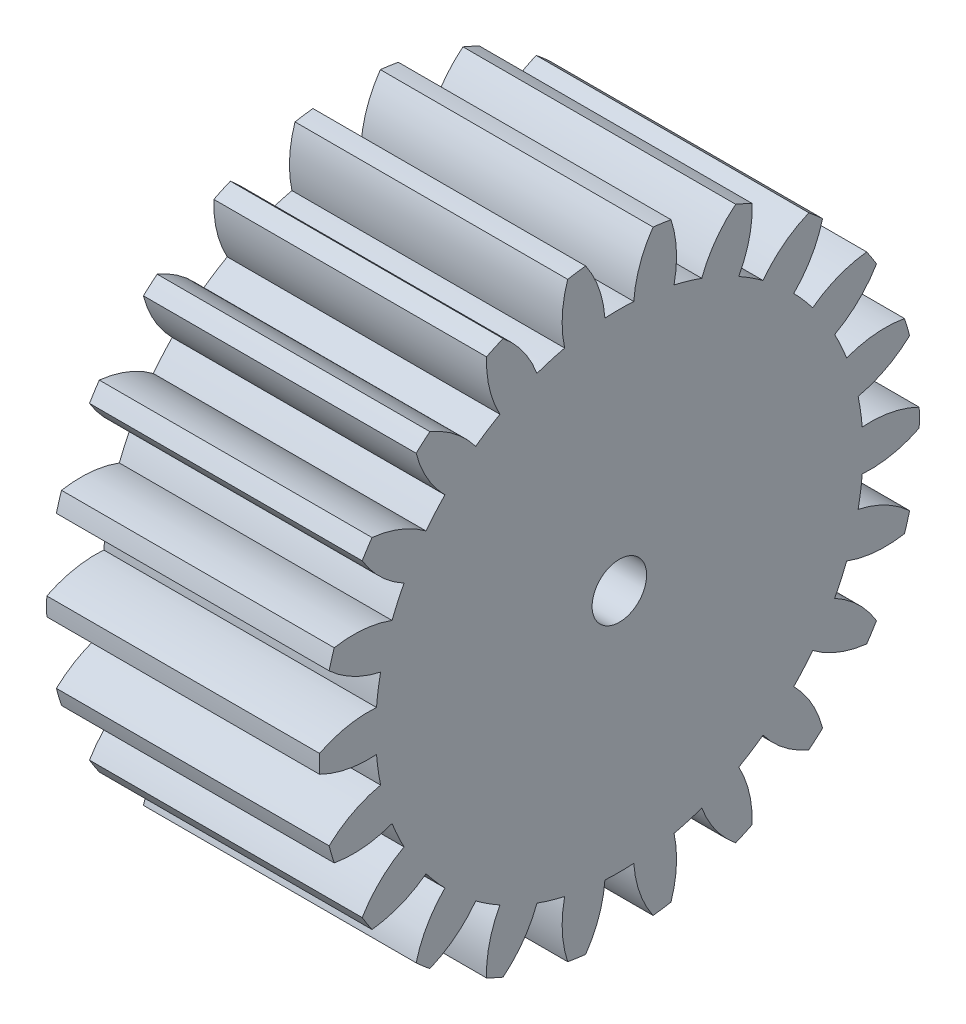
SolidWorks part; units mm, degrees
ref_plane "Plane1" through (0, 0, 0) normal (0, 0, 1) x (1, 0, 0)
ref_plane "Plane2" through (0, 0, 0) normal (0, 1, 0) x (1, 0, 0)
ref_plane "Plane3" through (0, 0, 0) normal (1, 0, 0) x (0, 0, -1)
sketch "HoldingSke" plane through (0, 0, 0) normal (0, 1, 0) x (1, 0, 0)
  line L0 (0, 0) -> (0.6743, -0.2724)
  line L1 (-15, 0) -> (100, 0) construction
  line L2 (0, 0) -> (-2.1039, 2.3779)
  line L3 (0, 0) -> (-11.863, 4.5341)
  line L4 (0, 0) -> (8.0072, 3.2351)
  line L5 (0, 0) -> (-46.8476, -17.4728)
  line L6 (0, 0) -> (-12.4344, -8.3896)
  line L7 (-2.1039, 2.3779) -> (8.6586, 51.2059)
  line L8 (-76.2, 54.61) -> (-75.7, 54.61)
  line L9 (-67.7845, 28.3722) -> (-49.3413, 33.142)
  line L10 (-76.2, 71.12) -> (104.1128, 71.12)
  line L11 (0, 0) -> (-15, 0)
  line L12 (-76.2, 101.6) -> (-76.151, 101.6)
  line L13 (24.9733, 27.94) -> (52.9518, 28.4284)
  line L14 (24.9733, 27.94) -> (24.9743, 27.94)
  line L15 (24.9733, 27.94) -> (100.4006, 29.5858)
  line L16 (-63.627, -1.375) -> (-12.827, -1.375)
  circle A0 centre (0, 0) radius 1.5
  circle A1 centre (0, 0) radius 13.4053
  circle A2 centre (0, 0) radius 37.5
  circle A3 centre (0, 0) radius 1.5
  dimension "MHD" = 26.8105
  dimension "Hub_dia" = 75
  dimension "Num_teeth" = 22
  dimension "Pitch" = 0.7273
  dimension "Overall_len" = 50
  dimension "Show_teeth" = 22
  dimension "Thickness" = 15
  dimension "OAL" = 50.0001
  dimension "Ap" = 14.5
  dimension "H" = 19.05
  dimension "Pitch_radius" = 180.3128
  dimension "Width" = 15
  dimension "Backlash" = 0.049
  dimension "Addendum_fac" = 1
  dimension "Dedendum_fac" = 1.25
  dimension "Clearance_fac" = 0.25
  dimension "Dedendum_add" = 0.001
  dimension "Module" = 1.375
sketch "BasProSke" plane through (0, 0, 0) normal (0, 1, 0) x (1, 0, 0)
  line L0 (-10, 0) -> (60, 0) construction
  line L1 (0, 0) -> (0, 16.5)
  line L2 (0, 0) -> (15, 0)
  line L3 (15, 0) -> (15, 16.5)
  line L4 (15, 16.5) -> (0, 16.5)
  dimension "Thickness" = 15
  dimension "Diameter" = 33
revolve "Base-Revolve" add sketch "BasProSke" angle 360 about L0
sketch "TooCutSke" plane through (0, 0, 0) normal (1, 0, 0) x (0, 0, -1)
  line L1 (0, 0) -> (0, 107) construction
  line L2 (0, 0) -> (-1.1647, 15.0801) construction
  line L3 (0, 0) -> (-4.2957, 29.8775) construction
  line L4 (-1.1647, 15.0801) -> (-2.1479, 14.9387) construction
  arc A0 (0.7938, 13.3817) -> (-0.7938, 13.3817) centre (0, 0) ccw
  arc A1 (1.8697, 16.4193) -> (-1.8697, 16.4193) centre (0, 0) ccw
  circle A2 centre (0, 0) radius 15.125 construction
  circle A3 centre (0, 0) radius 14.6432 construction
  arc A4 (-0.7938, 13.3817) -> (-1.8697, 16.4193) centre (-6.8287, 12.9535) ccw
  arc A5 (1.8697, 16.4193) -> (0.7938, 13.3817) centre (6.8287, 12.9535) ccw
  dimension "Root_dia" = 26.8105
  dimension "Overcut_dia" = 33.0508
  dimension "Pitch_dia" = 30.25
  dimension "Base_dia" = 29.2865
  dimension "Flank_rad" = 6.05
  dimension "Half_ang" = 8.182
  dimension "Half_CT" = 0.9933
extrude "ToothCut" cut sketch "TooCutSke" along normal through all
fillet "Breaks" [suppressed] radius 0.0275
fillet "RootFillets" [suppressed] radius 0.3448
pattern_circular "TeethCuts" count 22 over 360 about axis through (0, 0, 0) along (1, 0, 0) of "ToothCut", "RootFillets", "Breaks"
sketch "HubNeaOneSke" plane through (0, 0, 0) normal (-1, 0, 0) x (0, 0, 1)
  circle A0 centre (0, 0) radius 13.4053
  dimension "Diameter" = 26.8105
extrude "HubNearOne" [suppressed] add sketch "HubNeaOneSke" along normal blind 35.0001
sketch "HubNeaBotSke" plane through (0, 0, 0) normal (-1, 0, 0) x (0, 0, 1)
  circle A0 centre (0, 0) radius 13.4053
  dimension "Diameter" = 26.8105
extrude "HubNearBoth" [suppressed] add sketch "HubNeaBotSke" along normal blind 17.5
ref_plane "FarPln" through (15, 0, 0) normal (1, 0, 0) x (0, 0, -1)
sketch "HubFarSke" plane through (15, 0, 0) normal (1, 0, 0) x (0, 0, -1)
  circle A0 centre (0, 0) radius 13.4053
  dimension "Diameter" = 26.8105
extrude "HubFar" [suppressed] add sketch "HubFarSke" along normal blind 17.5
sketch "BorSke" plane through (0, 0, 0) normal (1, 0, 0) x (0, 0, -1)
  circle A0 centre (0, 0) radius 1.5
extrude "Bore" cut sketch "BorSke" along normal mid plane 100.0001
sketch "KeySke" plane through (0, 0, 0) normal (1, 0, 0) x (0, 0, -1)
  line L0 (-0.6, 0) -> (-0.6, 2)
  line L1 (-0.6, 2) -> (0.6, 2)
  line L2 (0.6, 2) -> (0.6, 0)
  line L3 (0, 0) -> (0, 34) construction
  line L4 (-0.6, 0) -> (0.6, 0)
extrude "Keyway" [suppressed] cut sketch "KeySke" along normal mid plane 100.0001
pattern_circular "Keyway2" [suppressed] count 2 every 90 about axis through (-10, 0, 0) along (1, 0, 0)
equation "' \"Module@HoldingSke\" = 6.35"
equation "' \"Num_teeth@HoldingSke\" = 12"
equation "' \"Ap@HoldingSke\" =  20"
equation "' \"Ap@HoldingSke\" = 20"
equation "' \"Width@HoldingSke\" = 0.5 * 25.4"
equation "' \"Hub_dia@HoldingSke\"= 1 * 25.4"
equation "' \"Hub_dia@HoldingSke\" = 1 * 25.4"
equation "' \"Overall_len@HoldingSke\" = 1.0 * 25.4"
equation "' \"Bore@HoldingSke\" = 0.75 * 25.4"
equation "' \"T_dim@HoldingSke\" = 0.1 * 25.4"
equation "' \"Width@KeySke\" = 0.25 * 25.4"
equation "' \"Show_teeth@HoldingSke\" = 13"
equation "' \"Backlash@HoldingSke\" = 0.009 * 25.4"
equation "' \"Addendum_fac@HoldingSke\" = 1.0"
equation "' \"Dedendum_fac@HoldingSke\" = 1.25"
equation "' \"Dedendum_add@HoldingSke\" = 0.00005 * 25.4"
equation "' \"Clearance_fac@HoldingSke\" = 0.25"
equation "\"Pitch@HoldingSke\" = 1 / \"Module@HoldingSke\""
equation "\"Overcut_dia@TooCutSke\" = (\"Num_teeth@HoldingSke\" + 2 * \"Addendum_fac@HoldingSke\") / \"Pitch@HoldingSke\" + 0.002 * 25.4"
equation "\"Pitch_dia@TooCutSke\" = \"Num_teeth@HoldingSke\" / \"Pitch@HoldingSke\""
equation "\"Base_dia@TooCutSke\" = \"Num_teeth@HoldingSke\" / \"Pitch@HoldingSke\" * cos((\"Ap@HoldingSke\"  * 3.14159265 / 180))"
equation "\"Root_dia@TooCutSke\" = (\"Num_teeth@HoldingSke\" + 2) / \"Pitch@HoldingSke\" - 2 * (\"Addendum_fac@HoldingSke\" + \"Dedendum_fac@HoldingSke\") / \"Pitch@HoldingSke\" - \"Dedendum_add@HoldingSke\" * 2"
equation "\"Half_ang@TooCutSke\" = 180 / \"Num_teeth@HoldingSke\""
equation "\"Half_CT@TooCutSke\" = \"Num_teeth@HoldingSke\" / \"Pitch@HoldingSke\" * sin((3.14159265 / 2 / \"Num_teeth@HoldingSke\")) / 2 - 7 * \"Backlash@HoldingSke\" / 4"
equation "\"Flank_rad@TooCutSke\" = \"Num_teeth@HoldingSke\" / \"Pitch@HoldingSke\" / 5"
equation "\"Radius@RootFillets\" = \"Clearance_fac@HoldingSke\" / \"Pitch@HoldingSke\" + \"Dedendum_add@HoldingSke\""
equation "\"Break_rad@Breaks\" = 0.02 / \"Pitch@HoldingSke\""
equation "\"Thickness@HoldingSke\" = \"Width@HoldingSke\""
equation "\"OAL@HoldingSke\" = \"Thickness@HoldingSke\""
equation "\"MHD@HoldingSke\" = (\"Num_teeth@HoldingSke\" + 2) / \"Pitch@HoldingSke\" - 2 * (\"Addendum_fac@HoldingSke\" + \"Dedendum_fac@HoldingSke\")  / \"Pitch@HoldingSke\" - \"Dedendum_add@HoldingSke\" * 2"
equation "\"MBD@HoldingSke\" = (\"Num_teeth@HoldingSke\" + 2) / \"Pitch@HoldingSke\" - 2 * (\"Addendum_fac@HoldingSke\" + \"Dedendum_fac@HoldingSke\")  / \"Pitch@HoldingSke\" - \"Dedendum_add@HoldingSke\" * 2 - 0.002 * 25.4"
equation "\"MHD@HoldingSke\" = ((sgn( \"MHD@HoldingSke\" - \"Hub_dia@HoldingSke\" )-1)*( \"MHD@HoldingSke\" - \"Hub_dia@HoldingSke\" ))/-2+ \"Hub_dia@HoldingSke\""
equation "\"MBD@HoldingSke\" = ((sgn( \"MBD@HoldingSke\" - \"Bore@HoldingSke\" )-1)*( \"MBD@HoldingSke\" - \"Bore@HoldingSke\" ))/-2+ \"Bore@HoldingSke\""
equation "\"OAL@HoldingSke\" = ((sgn( \"OAL@HoldingSke\" - \"Overall_len@HoldingSke\" )+1)*( \"OAL@HoldingSke\" - \"Overall_len@HoldingSke\" ))/2 + \"Overall_len@HoldingSke\" + 0.000002 * 25.4"
equation "\"Num_teeth@TeethCuts\" = int( \"Show_teeth@HoldingSke\" ) + 1"
equation "\"Num_teeth@TeethCuts\" = ((sgn( \"Num_teeth@TeethCuts\" - \"Num_teeth@HoldingSke\" )-1)*( \"Num_teeth@TeethCuts\" - \"Num_teeth@HoldingSke\" ))/-2+ \"Num_teeth@HoldingSke\""
equation "\"Num_teeth@TeethCuts\" = ((sgn( \"Num_teeth@TeethCuts\" - 2.0)+1)*( \"Num_teeth@TeethCuts\" - 2.0))/2 +2.0"
equation "\"Angle@TeethCuts\" = 360.0 / \"Num_teeth@HoldingSke\""
equation "\"Diameter@BasProSke\" = (\"Num_teeth@HoldingSke\" + 2 * \"Addendum_fac@HoldingSke\") / \"Pitch@HoldingSke\""
equation "\"Thickness@BasProSke\"  = \"Thickness@HoldingSke\""
equation "' \"Fillet_rad@BasProSke\" =  \"Thickness@HoldingSke\" * 0.05"
equation "' \"Fillet_rad@BasProSke\" = \"Thickness@HoldingSke\" * 0.05"
equation "\"MHD@HoldingSke\" = ((sgn( \"MHD@HoldingSke\" - \"Root_dia@TooCutSke\" )-1)*( \"MHD@HoldingSke\" - \"Root_dia@TooCutSke\" ))/-2+ \"Root_dia@TooCutSke\""
equation "\"Diameter@HubNeaOneSke\" = \"MHD@HoldingSke\""
equation "\"Length@HubNearOne\" = \"OAL@HoldingSke\" - \"Thickness@BasProSke\""
equation "\"Diameter@HubNeaBotSke\" = \"MHD@HoldingSke\""
equation "\"Length@HubNearBoth\" = ( \"OAL@HoldingSke\" - \"Thickness@BasProSke\" ) / 2.0"
equation "\"Thickness@FarPln\" = \"Thickness@BasProSke\""
equation "\"Diameter@HubFarSke\" = \"MHD@HoldingSke\""
equation "\"Length@HubFar\" = ( \"OAL@HoldingSke\" - \"Thickness@BasProSke\" ) / 2.0"
equation "\"Diameter@BorSke\" = \"MBD@HoldingSke\""
equation "\"D1@Bore\" = \"OAL@HoldingSke\" * 2.0"
equation "\"D1@Keyway\" = \"OAL@HoldingSke\" * 2.0"
equation "\"Offset@KeySke\" = \"T_dim@HoldingSke\" + \"MBD@HoldingSke\" / 2.0"
